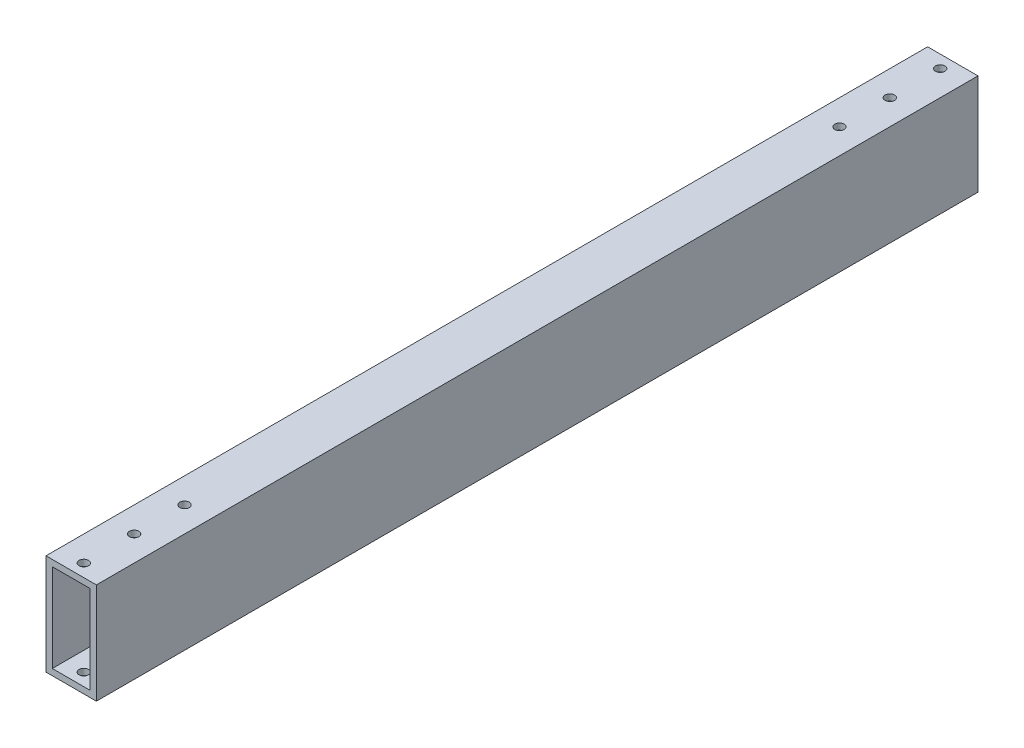
SolidWorks part; units mm, degrees
ref_plane "Front Plane" through (0, 0, 0) normal (0, 0, 1) x (1, 0, 0)
ref_plane "Top Plane" through (0, 0, 0) normal (0, 1, 0) x (1, 0, 0)
ref_plane "Right Plane" through (0, 0, 0) normal (1, 0, 0) x (0, 0, -1)
sketch "Sketch1" plane through (0, 0, 0) normal (0, 0, 1) x (1, 0, 0)
  line L1 (-12.7, 25.4) -> (12.7, 25.4)
  line L2 (-12.7, 25.4) -> (-12.7, -25.4)
  line L3 (-12.7, -25.4) -> (12.7, -25.4)
  line L4 (12.7, 25.4) -> (12.7, -25.4)
  line L5 (-12.7, 25.4) -> (12.7, -25.4) construction
  line L6 (-12.7, -25.4) -> (12.7, 25.4) construction
  point P0 (0, 0)
  dimension "D1" = 25.4
  dimension "D2" = 50.8
extrude "Boss-Extrude1" add sketch "Sketch1" along normal blind 444.5
shell "Shell1" thickness 3.175
sketch "Sketch2" plane through (0, 25.4, 0) normal (0, 1, 0) x (1, 0, 0)
  line L0 (12.7, 0) -> (-12.7, 0) construction
  line L1 (12.7, -222.25) -> (-14.2289, -222.25) construction
  line L2 (12.7, -444.5) -> (12.7, 0) construction
  circle A0 centre (0, -6.35) radius 2.3812
  circle A3 centre (0, -31.75) radius 2.3812
  circle A4 centre (0, -57.15) radius 2.3812
  circle A5 centre (0, -387.35) radius 2.3812
  circle A6 centre (0, -412.75) radius 2.3812
  circle A7 centre (0, -438.15) radius 2.3813
  dimension "D1" = 4.7625
  dimension "D2" = 6.35
  dimension "D3" = 3
extrude "Cut-Extrude1" cut sketch "Sketch2" against normal through all
